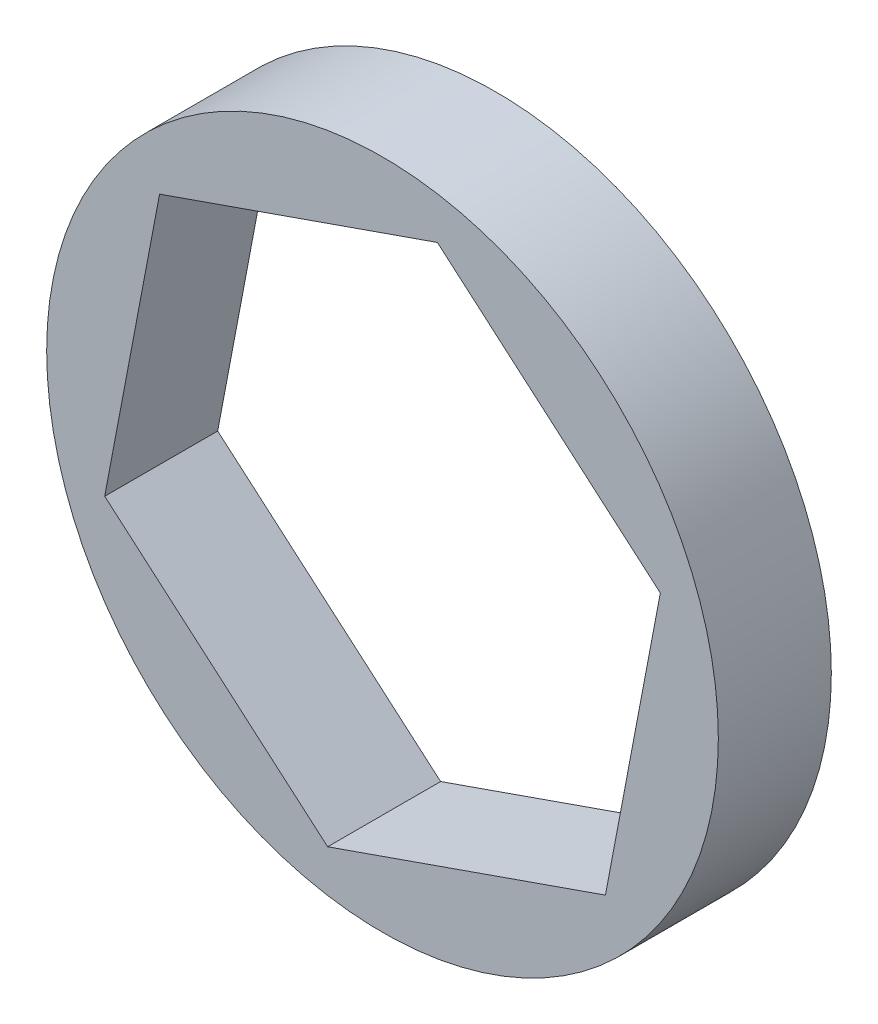
SolidWorks part; units mm, degrees
ref_plane "Front Plane" through (0, 0, 0) normal (0, 0, 1) x (1, 0, 0)
ref_plane "Top Plane" through (0, 0, 0) normal (0, 1, 0) x (1, 0, 0)
ref_plane "Right Plane" through (0, 0, 0) normal (1, 0, 0) x (0, 0, -1)
sketch "Sketch1" plane through (0, 0, 0) normal (0, 0, 1) x (1, 0, 0)
  line L1 (-5.6425, 4.8613) -> (-7.0312, -2.4559)
  line L2 (-7.0312, -2.4559) -> (-1.3887, -7.3172)
  line L3 (-1.3887, -7.3172) -> (5.6425, -4.8613)
  line L4 (5.6425, -4.8613) -> (7.0312, 2.4559)
  line L5 (7.0312, 2.4559) -> (1.3887, 7.3172)
  line L6 (1.3887, 7.3172) -> (-5.6425, 4.8613)
  circle A0 centre (0, 0) radius 6.45 construction
  circle A1 centre (0, 0) radius 8.5
  dimension "D1" = 17
  dimension "D2" = 12.9
extrude "Boss-Extrude1" add sketch "Sketch1" along normal blind 2.86
